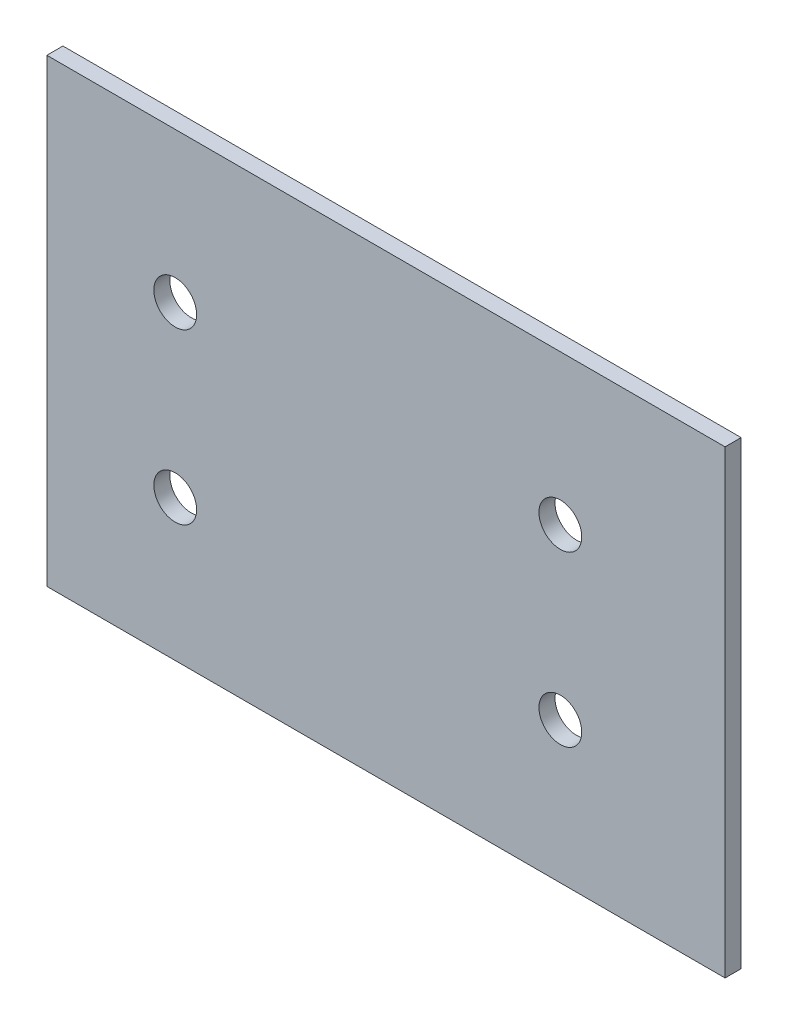
SolidWorks part; units mm, degrees
ref_plane "Front Plane" through (0, 0, 0) normal (0, 0, 1) x (1, 0, 0)
ref_plane "Top Plane" through (0, 0, 0) normal (0, 1, 0) x (1, 0, 0)
ref_plane "Right Plane" through (0, 0, 0) normal (1, 0, 0) x (0, 0, -1)
sketch "Sketch1" plane through (0, 0, 0) normal (0, 0, 1) x (1, 0, 0)
  line L1 (-40.259, 27.305) -> (40.259, 27.305)
  line L2 (-40.259, 27.305) -> (-40.259, -27.305)
  line L3 (-40.259, -27.305) -> (40.259, -27.305)
  line L4 (40.259, 27.305) -> (40.259, -27.305)
  line L5 (-40.259, 27.305) -> (40.259, -27.305) construction
  line L6 (-40.259, -27.305) -> (40.259, 27.305) construction
  point P0 (0, 0)
  dimension "D13" = 80.518
  dimension "D2" = 54.61
extrude "Boss-Extrude1" add sketch "Sketch1" along normal blind 1.905
sketch "Sketch2" plane through (0, 0, 1.905) normal (0, 0, 1) x (1, 0, 0)
  line L0 (40.259, 27.305) -> (-40.259, 27.305) construction
  line L1 (-40.259, 27.305) -> (-40.259, -27.305) construction
  circle A0 centre (-25.019, 9.525) radius 2.54
  circle A1 centre (-25.019, -10.541) radius 2.54
  circle A2 centre (20.701, 9.525) radius 2.54
  circle A3 centre (20.701, -10.541) radius 2.54
  dimension "D1" = 5.08
  dimension "D2" = 20.066
  dimension "D3" = 17.78
  dimension "D4" = 15.24
  dimension "D5" = 45.72
extrude "Cut-Extrude1" cut sketch "Sketch2" against normal through all
